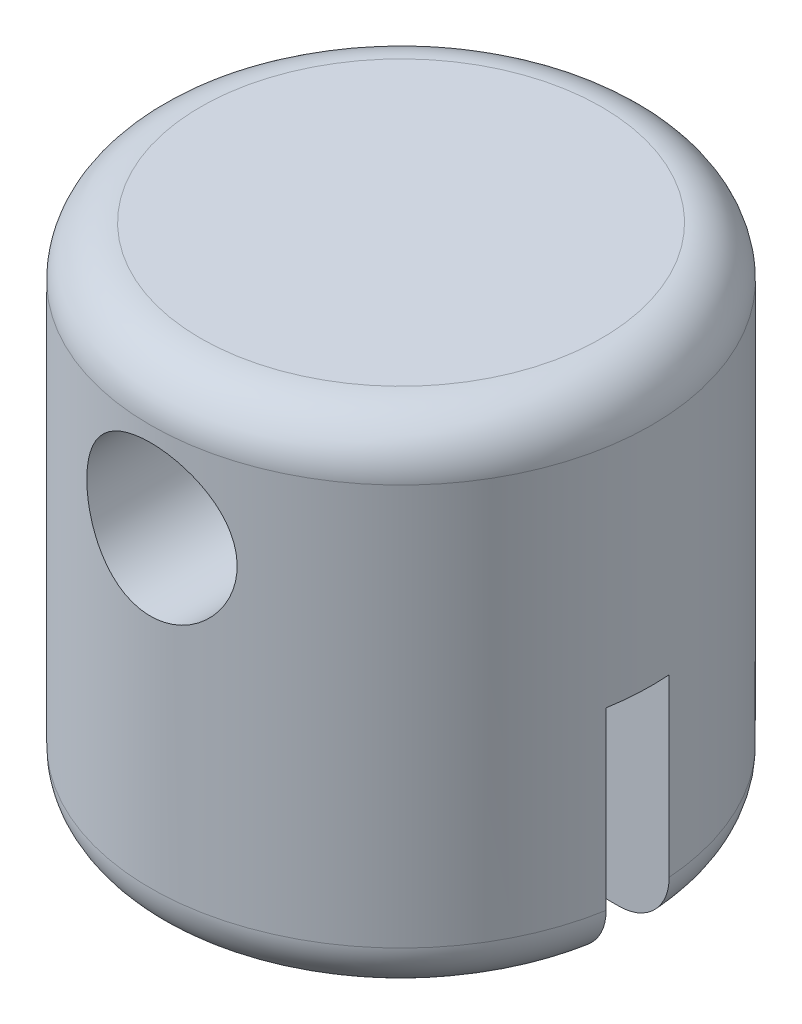
SolidWorks part; units mm, degrees
ref_plane "Front Plane" through (0, 0, 0) normal (0, 0, 1) x (1, 0, 0)
ref_plane "Top Plane" through (0, 0, 0) normal (0, 1, 0) x (1, 0, 0)
ref_plane "Right Plane" through (0, 0, 0) normal (1, 0, 0) x (0, 0, -1)
sketch "Sketch1" plane through (0, 0, 0) normal (0, 1, 0) x (1, 0, 0)
  circle A0 centre (0, 0) radius 12.7
  dimension "D1" = 25.4
extrude "Boss-Extrude1" add sketch "Sketch1" along normal blind 25.4
sketch "Sketch2" plane through (0, 0, 0) normal (0, 0, 1) x (1, 0, 0)
  circle A0 centre (0, 18.2861) radius 3.81
  dimension "D1" = 7.62
extrude "Cut-Extrude1" cut sketch "Sketch2" along normal mid plane 50.8
sketch "Sketch3" plane through (0, 0, 0) normal (1, 0, 0) x (0, 0, -1)
  line L0 (-12.7, 0) -> (12.7, 0) construction
  line L1 (-2.128, 0) -> (0.92, 0)
  line L2 (-2.128, 0) -> (-2.128, 11.43)
  line L3 (-2.128, 11.43) -> (0.92, 11.43)
  line L4 (0.92, 0) -> (0.92, 11.43)
  dimension "D1" = 3.048
  dimension "D2" = 11.43
extrude "Cut-Extrude2" cut sketch "Sketch3" against normal mid plane 50.8
fillet "Fillet1" radius 2.54 3 edges at (0, 0, 12.7) (0, 0, -12.7) (0, 25.4, 12.7)
